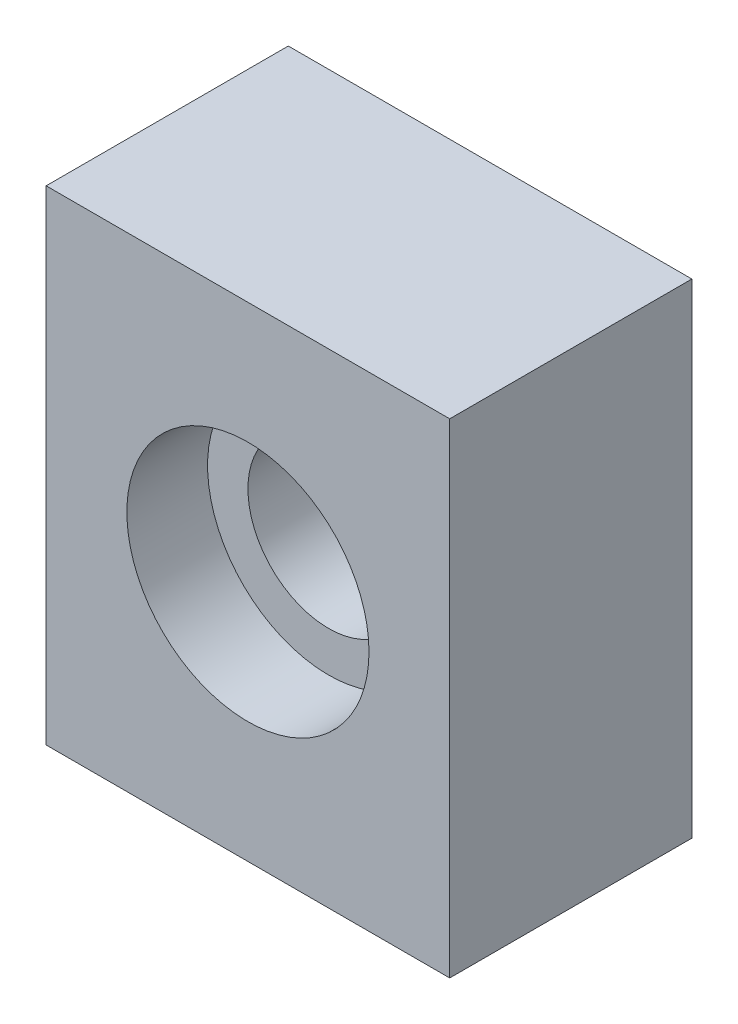
SolidWorks part; units mm, degrees
ref_plane "Plan de face" through (0, 0, 0) normal (0, 0, 1) x (1, 0, 0)
ref_plane "Plan de dessus" through (0, 0, 0) normal (0, 1, 0) x (1, 0, 0)
ref_plane "Plan de droite" through (0, 0, 0) normal (1, 0, 0) x (0, 0, -1)
sketch "Esquisse1" plane through (0, 0, 0) normal (0, 0, 1) x (1, 0, 0)
  line L0 (-25, 30) -> (25, -30) construction
  line L1 (-25, 30) -> (25, 30)
  line L2 (-25, 30) -> (-25, -30)
  line L3 (-25, -30) -> (25, -30)
  line L4 (25, 30) -> (25, -30)
  circle A0 centre (0, 0) radius 10
  dimension "D3" = 20
  dimension "D1" = 50
  dimension "D2" = 60
extrude "Boss.-Extru.1" add sketch "Esquisse1" along normal blind 30
sketch "Esquisse2" plane through (0, 0, 30) normal (0, 0, 1) x (1, 0, 0)
  circle A0 centre (0, 0) radius 15
  dimension "D1" = 30
extrude "Enlèv. mat.-Extru.1" cut sketch "Esquisse2" against normal blind 10
